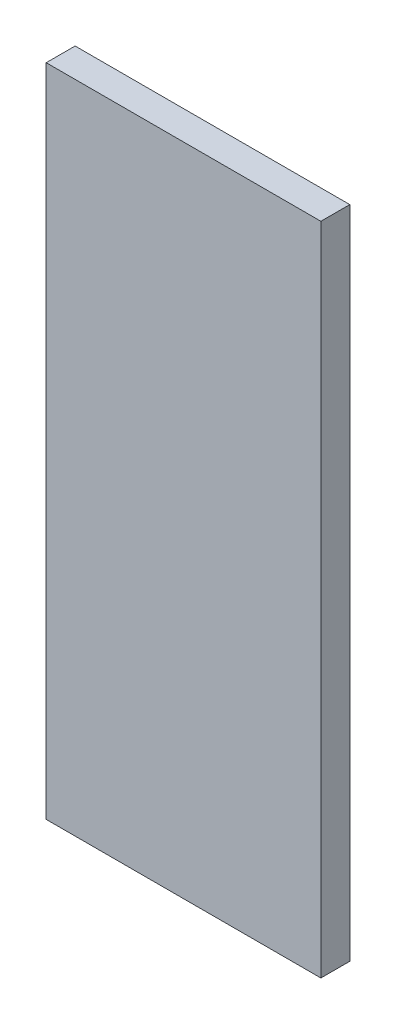
SolidWorks part; units mm, degrees
material "Polyurethane Foam Rigid"
ref_plane "Front Plane" through (0, 0, 0) normal (0, 0, 1) x (1, 0, 0)
ref_plane "Top Plane" through (0, 0, 0) normal (0, 1, 0) x (1, 0, 0)
ref_plane "Right Plane" through (0, 0, 0) normal (1, 0, 0) x (0, 0, -1)
sketch "Sketch1" plane through (0, 0, 0) normal (0, 0, 1) x (1, 0, 0)
  line L1 (-361.95, -863.6) -> (361.95, -863.6)
  line L2 (-361.95, -863.6) -> (-361.95, 863.6)
  line L3 (-361.95, 863.6) -> (361.95, 863.6)
  line L4 (361.95, -863.6) -> (361.95, 863.6)
  line L5 (-361.95, -863.6) -> (361.95, 863.6) construction
  line L6 (-361.95, 863.6) -> (361.95, -863.6) construction
  point P0 (0, 0)
extrude "Boss-Extrude1" add sketch "Sketch1" along normal blind 76.2
